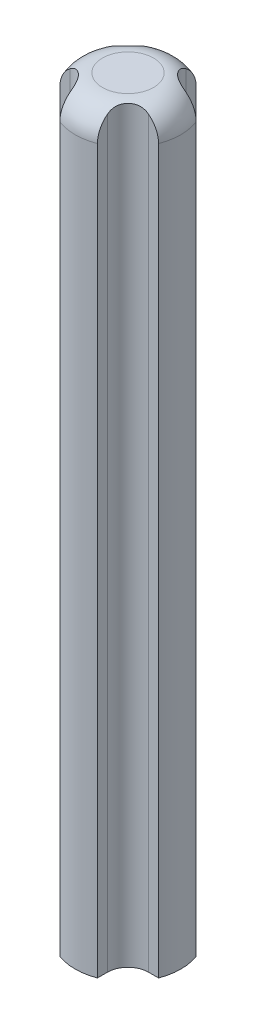
SolidWorks part; units mm, degrees
ref_plane "Front Plane" through (0, 0, 0) normal (0, 0, 1) x (1, 0, 0)
ref_plane "Top Plane" through (0, 0, 0) normal (0, 1, 0) x (1, 0, 0)
ref_plane "Right Plane" through (0, 0, 0) normal (1, 0, 0) x (0, 0, -1)
sketch "Sketch1" plane through (0, 0, 0) normal (0, 1, 0) x (1, 0, 0)
  circle A0 centre (0, 0) radius 3.875
  dimension "D1" = 7.75
extrude "Boss-Extrude1" add sketch "Sketch1" along normal blind 55
fillet "Fillet1" radius 2 1 edges at (0, 55, 3.875)
sketch "Sketch2" plane through (0, 55, 0) normal (0, 1, 0) x (1, 0, 0)
  line L0 (0, 0) -> (1.3789, -1.3789) construction
  line L1 (1.3789, -1.3789) -> (0, -1.3789) construction
  line L2 (1.3789, -1.3789) -> (3.8789, -1.3789)
  line L3 (1.3789, -1.3789) -> (1.3789, -3.8789)
  line L4 (1.3789, -3.8789) -> (3.8789, -3.8789)
  line L5 (3.8789, -1.3789) -> (3.8789, -3.8789)
  line L6 (0, -1.3789) -> (0, 0) construction
  dimension "D1" = 1.95
  dimension "D2" = 2.5
extrude "Cut-Extrude1" cut sketch "Sketch2" against normal through all
pattern_circular "CirPattern1" count 4 over 360 about axis through (0, 0, 0) along (0, 1, 0) of "Cut-Extrude1"
fillet "Fillet2" radius 1.5 4 edges at (1.3789, 27.4993, -1.3789) (-1.3789, 27.4993, -1.3789) (-1.3789, 27.4993, 1.3789) (1.3789, 27.4993, 1.3789)
